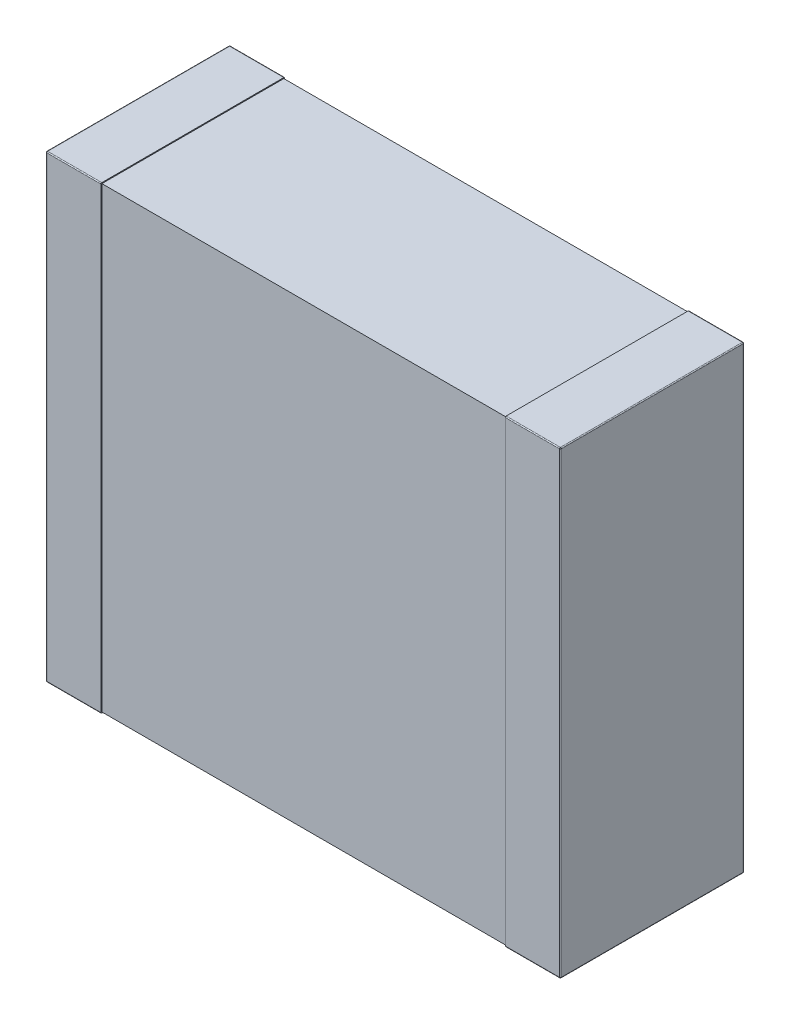
SolidWorks part; units mm, degrees
ref_plane "Front Plane" through (0, 0, 0) normal (0, 0, 1) x (1, 0, 0)
ref_plane "Top Plane" through (0, 0, 0) normal (0, 1, 0) x (1, 0, 0)
ref_plane "Right Plane" through (0, 0, 0) normal (1, 0, 0) x (0, 0, -1)
sketch "Sketch1" plane through (0, 0, 0) normal (0, 0, 1) x (1, 0, 0)
  line L0 (0, 0.15) -> (0, -0.15) construction
  line L1 (-2.8, 0) -> (0, 0) construction
  line L3 (-2.8, 2.5) -> (-2.2, 2.5)
  line L4 (-2.8, 2.5) -> (-2.8, -2.5)
  line L5 (-2.8, -2.5) -> (-2.2, -2.5)
  line L6 (-2.2, 2.5) -> (-2.2, -2.5)
  dimension "BANDWIDTH" = 0.6
  dimension "WIDTH" = 5
  dimension "LENGTH-HALF" = 2.8
extrude "THICKNESS" add sketch "Sketch1" along normal blind 2
fillet "Fillet1" radius 0.01 8 edges at (-2.8, 0, 0) (-2.5, 2.5, 0) (-2.8, 2.5, 1) (-2.5, -2.5, 0) (-2.8, -2.5, 1) (-2.8, 0, 2) (-2.5, 2.5, 2) (-2.5, -2.5, 2)
sketch "Sketch2" plane through (0, 0, 0) normal (1, 0, 0) x (0, 0, -1)
  line L0 (0, -2.49) -> (0, 2.49) construction
  line L1 (-1.99, 2.49) -> (-0.01, 2.49)
  line L2 (-1.99, 2.49) -> (-1.99, -2.49)
  line L3 (-1.99, -2.49) -> (-0.01, -2.49)
  line L4 (-0.01, 2.49) -> (-0.01, -2.49)
  line L6 (-1.99, 2.5) -> (-0.01, 2.5) construction
  line L7 (-1.99, -2.5) -> (-0.01, -2.5) construction
  line L8 (-2, -2.49) -> (-2, 2.49) construction
  point P6 (0, 0.99)
  point P7 (0.2564, -2.2936)
  point P8 (0.9288, -0.1384)
  point P9 (-2.49, -0.1384)
  point P12 (-1.6889, 2.0153)
  dimension "D1" = 0.01
  dimension "D2" = 0.01
  dimension "D3" = 0.01
  dimension "D4" = 0.01
extrude "Boss-Extrude2" add sketch "Sketch2" against normal up to surface (2.2 mm away) up to face at (-2.2, 0, 1)
mirror "Mirror3" about plane through (0, 0, 0) normal (1, 0, 0) of "Boss-Extrude2", "Fillet1", "THICKNESS"
